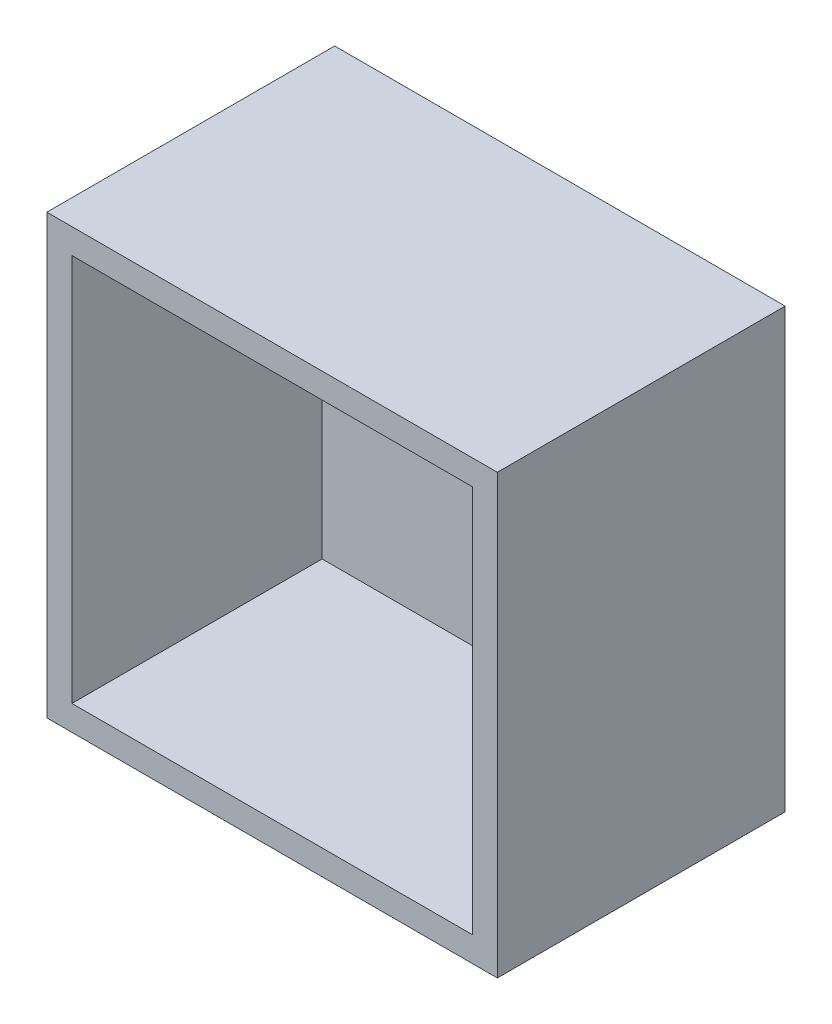
SolidWorks part; units mm, degrees
ref_plane "Plan de face" through (0, 0, 0) normal (0, 0, 1) x (1, 0, 0)
ref_plane "Plan de dessus" through (0, 0, 0) normal (0, 1, 0) x (1, 0, 0)
ref_plane "Plan de droite" through (0, 0, 0) normal (1, 0, 0) x (0, 0, -1)
sketch "Esquisse1" plane through (0, 0, 0) normal (0, 0, 1) x (1, 0, 0)
  line L1 (0, 0) -> (-32, 0)
  line L2 (0, 0) -> (0, 31)
  line L3 (0, 31) -> (-32, 31)
  line L4 (-32, 0) -> (-32, 31)
  dimension "D1" = 32
  dimension "D2" = 31
extrude "Boss.-Extru.1" add sketch "Esquisse1" along normal blind 3
sketch "Esquisse2" plane through (0, 0, 3) normal (0, 0, 1) x (1, 0, 0)
  line L1 (-34, 33) -> (2, 33)
  line L2 (-34, 33) -> (-34, -2)
  line L3 (-34, -2) -> (2, -2)
  line L4 (2, 33) -> (2, -2)
  line L5 (-32, 31) -> (0, 31)
  line L6 (-32, 31) -> (-32, 0)
  line L7 (-32, 0) -> (0, 0)
  line L8 (0, 31) -> (0, 0)
  dimension "D1" = 2
  dimension "D2" = 2
  dimension "D3" = 2
  dimension "D4" = 2
extrude "Boss.-Extru.2" add sketch "Esquisse2" along normal blind 20 and the other way blind 3
sketch "Esquisse3" plane through (0, 0, 3) normal (0, 0, 1) x (1, 0, 0)
  line L0 (-32, 31) -> (0, 0) construction
  line L1 (0, 31) -> (-32, 0) construction
  circle A0 centre (-24.9825, 24.2018) radius 1.5
  circle A1 centre (-7.0265, 6.8069) radius 1.5
  dimension "D1" = 3
  dimension "D2" = 3
  dimension "D3" = 25
  dimension "D4" = 12.5
extrude "Enlèv. mat.-Extru.1" cut sketch "Esquisse3" against normal through all
sketch "Esquisse4" plane through (0, 0, 3) normal (0, 0, 1) x (1, 0, 0)
  circle A0 centre (-24.9825, 24.2018) radius 6
  circle A1 centre (-7.0265, 6.8069) radius 6
  dimension "D1" = 12
  dimension "D2" = 12
extrude "Enlèv. mat.-Extru.2" cut sketch "Esquisse4" against normal blind 1
